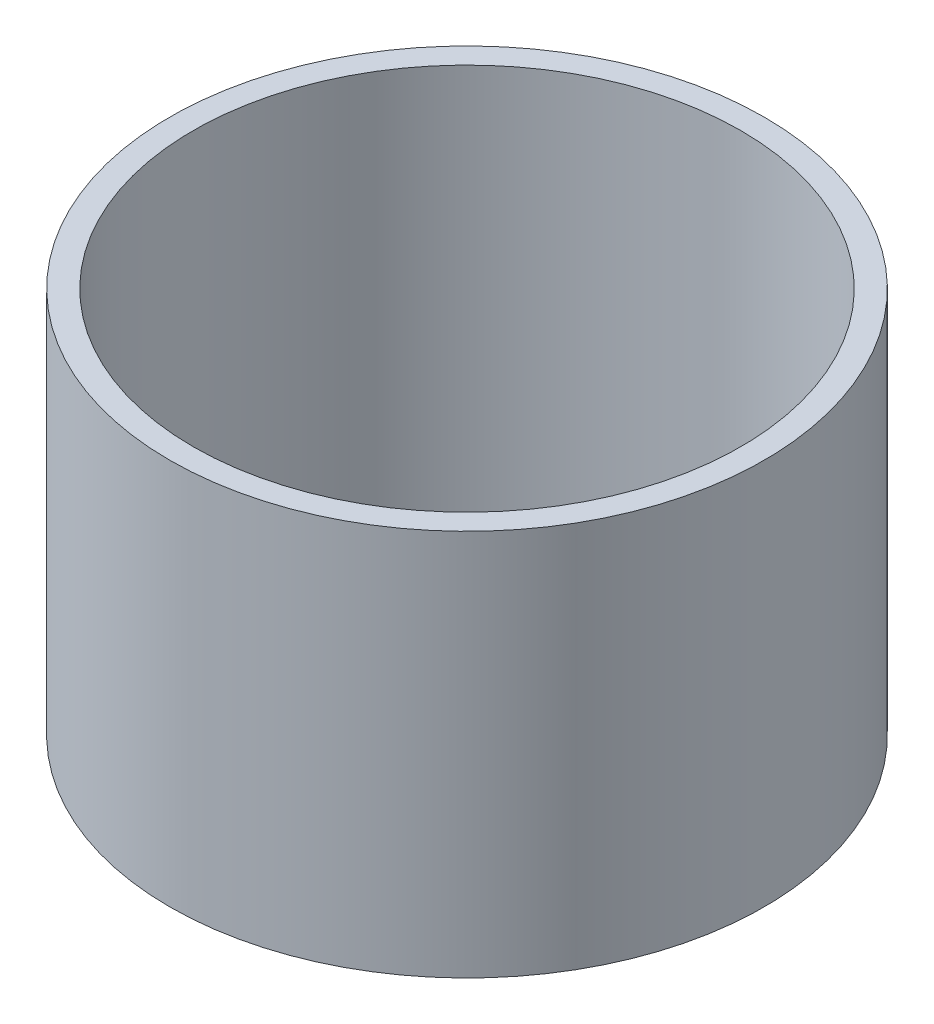
SolidWorks part; units mm, degrees
material "Chrome Stainless Steel"
ref_plane "Front Plane" through (0, 0, 0) normal (0, 0, 1) x (1, 0, 0)
ref_plane "Top Plane" through (0, 0, 0) normal (0, 1, 0) x (1, 0, 0)
ref_plane "Right Plane" through (0, 0, 0) normal (1, 0, 0) x (0, 0, -1)
ref_plane "Plane1" through (0, 0, 0) normal (0, 0, -1) x (-1, 0, 0)
sketch "Sketch1" plane through (0, 0, 0) normal (0, 0, -1) x (-1, 0, 0)
  line L0 (-7.747, 0) -> (-7.1374, 0)
  line L1 (-7.1374, 0) -> (-7.1374, 10.0838)
  line L2 (-7.1374, 10.0838) -> (-7.747, 10.0838)
  line L3 (-7.747, 10.0838) -> (-7.747, 0)
  line L4 (0, 0) -> (0, 10.0838) construction
revolve "Revolve1" add sketch "Sketch1" angle 360 about L4
